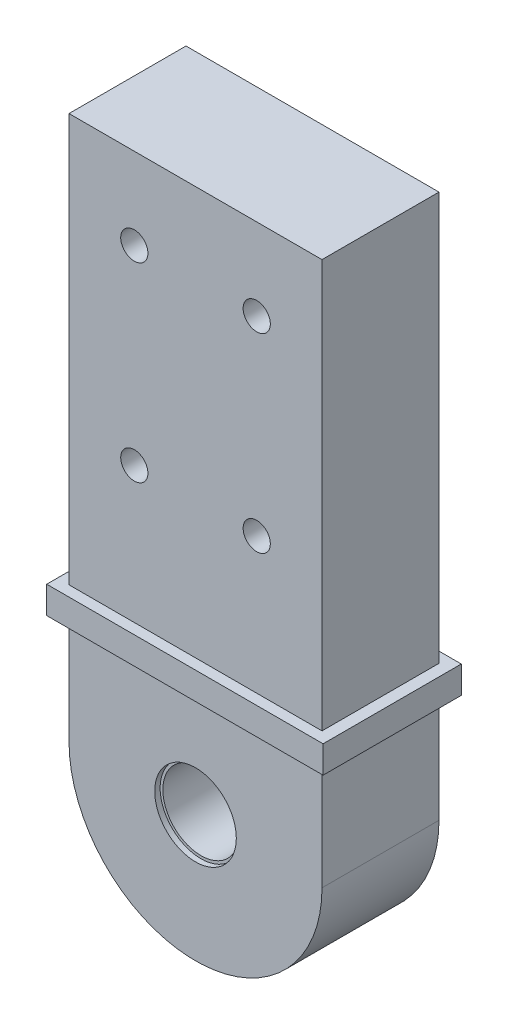
SolidWorks part; units mm, degrees
ref_plane "Front Plane" through (0, 0, 0) normal (0, 0, 1) x (1, 0, 0)
ref_plane "Top Plane" through (0, 0, 0) normal (0, 1, 0) x (1, 0, 0)
ref_plane "Right Plane" through (0, 0, 0) normal (1, 0, 0) x (0, 0, -1)
sketch "Sketch1" plane through (0, 0, 0) normal (0, 0, 1) x (1, 0, 0)
  line L0 (-23.25, 0) -> (-23.25, 100)
  line L1 (-23.25, 100) -> (23.25, 100)
  line L2 (23.25, 100) -> (23.25, 0)
  line L4 (-11.25, 85) -> (11.25, 85) construction
  line L5 (-11.25, 85) -> (-11.25, 50) construction
  line L6 (-11.25, 50) -> (11.25, 50) construction
  line L7 (11.25, 85) -> (11.25, 50) construction
  circle A0 centre (0, 0) radius 7
  arc A1 (-23.25, 0) -> (23.25, 0) centre (0, 0) ccw
  circle A2 centre (-11.25, 85) radius 2.5
  circle A3 centre (11.25, 85) radius 2.5
  circle A4 centre (11.25, 50) radius 2.5
  circle A5 centre (-11.25, 50) radius 2.5
  point P13 (0, 50)
  dimension "D1" = 14
  dimension "D4" = 5
  dimension "D2" = 46.5
  dimension "D3" = 100
  dimension "D5" = 35
  dimension "D6" = 15
  dimension "D7" = 22.5
extrude "Boss-Extrude1" add sketch "Sketch1" along normal blind 21.5
sketch "Sketch2" plane through (0, 0, 21.5) normal (0, 0, 1) x (1, 0, 0)
  circle A0 centre (0, 0) radius 7.5
  dimension "D1" = 15
extrude "Cut-Extrude1" cut sketch "Sketch2" against normal blind 1
sketch "Sketch3" plane through (0, 0, 0) normal (0, 0, -1) x (-1, 0, 0)
  circle A0 centre (0, 0) radius 7.5
  dimension "D1" = 15
extrude "Cut-Extrude2" cut sketch "Sketch3" against normal blind 1
sketch "Sketch4" plane through (0, 0, 21.5) normal (0, 0, 1) x (1, 0, 0)
  line L0 (-23.25, 24.981) -> (23.25, 24.981)
  line L1 (-23.25, 100) -> (-23.25, 0) construction
  line L2 (23.25, 0) -> (23.25, 100) construction
  circle A0 centre (11.25, 50) radius 2.5
  circle A1 centre (11.25, 50) radius 2.5 construction
  dimension "D1" = 25.019
ref_plane "Plane1" through (0, 24.981, 0) normal (0, 1, 0) x (1, 0, 0)
sketch "Sketch5" plane through (0, 24.981, 0) normal (0, 1, 0) x (1, 0, 0)
  line L4 (23.25, 0) -> (-23.25, 0)
  line L5 (-23.25, 0) -> (-23.25, -21.5)
  line L6 (-23.25, -21.5) -> (23.25, -21.5)
  line L7 (23.25, -21.5) -> (23.25, 0)
  line L8 (23.25, 0) -> (-23.25, 0)
  line L9 (-23.25, 0) -> (-23.25, -21.5)
  line L10 (-23.25, -21.5) -> (23.25, -21.5)
  line L11 (23.25, -21.5) -> (23.25, 0)
  line L20 (25.4, 1.95) -> (-25.4, 1.95)
  line L21 (-25.4, 1.95) -> (-25.4, -23.45)
  line L22 (-25.4, -23.45) -> (25.4, -23.45)
  line L23 (25.4, -23.45) -> (25.4, 1.95)
  point P2 (-25.4, -10.75)
  point P4 (-23.25, -10.75)
  point P6 (0, 1.95)
  dimension "D3" = 50.8
  dimension "D2" = 25.4
  dimension "D1" = 0
extrude "Boss-Extrude2" add sketch "Sketch5" against normal blind 5
